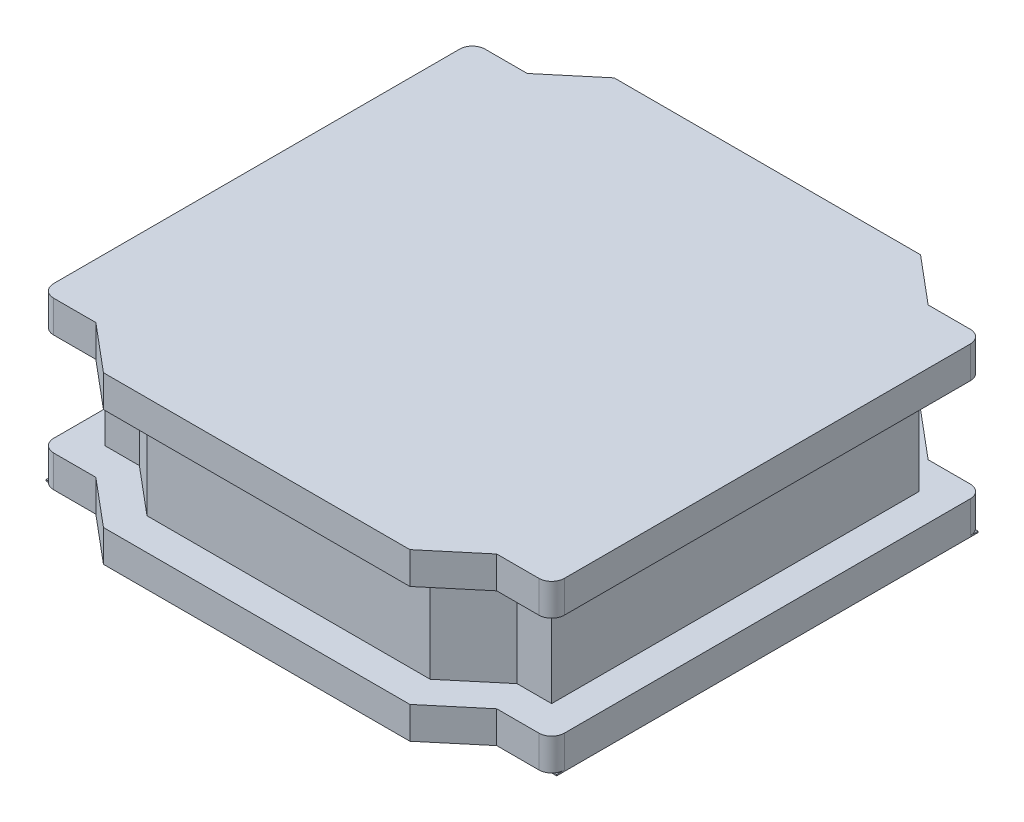
SolidWorks part; units mm, degrees
ref_plane "Alzado" through (0, 0, 0) normal (0, 0, 1) x (1, 0, 0)
ref_plane "Planta" through (0, 0, 0) normal (0, 1, 0) x (1, 0, 0)
ref_plane "Vista lateral" through (0, 0, 0) normal (1, 0, 0) x (0, 0, -1)
sketch "Croquis1" plane through (0, 0, 0) normal (0, 1, 0) x (1, 0, 0)
  line L0 (0.0879, 2.3156) -> (0.0879, -1.9186) construction
  line L1 (-3.3874, 0) -> (5.3457, 0) construction
  line L2 (1.2879, 2) -> (-1.1121, 2)
  line L3 (-1.1121, 2) -> (-1.4821, 1.6895)
  line L4 (-1.4821, 1.6895) -> (-1.8121, 1.6895)
  line L5 (-1.9121, 1.5895) -> (-1.9121, -1.5895)
  line L6 (2.0879, 1.5895) -> (2.0879, -1.5895)
  line L7 (1.658, 1.6895) -> (1.9879, 1.6895)
  line L8 (1.2879, 2) -> (1.658, 1.6895)
  line L9 (1.2879, -2) -> (1.658, -1.6895)
  line L10 (1.658, -1.6895) -> (1.9879, -1.6895)
  line L11 (-1.4821, -1.6895) -> (-1.8121, -1.6895)
  line L12 (-1.1121, -2) -> (-1.4821, -1.6895)
  line L13 (1.2879, -2) -> (-1.1121, -2)
  arc A0 (-1.8121, -1.6895) -> (-1.9121, -1.5895) centre (-1.8121, -1.5895) cw
  arc A1 (1.9879, -1.6895) -> (2.0879, -1.5895) centre (1.9879, -1.5895) ccw
  arc A2 (2.0879, 1.5895) -> (1.9879, 1.6895) centre (1.9879, 1.5895) ccw
  arc A3 (-1.8121, 1.6895) -> (-1.9121, 1.5895) centre (-1.8121, 1.5895) ccw
  point P14 (0.0879, 2)
  point P17 (2.0879, 0)
  point P18 (-1.9121, 0)
  point P20 (0.0879, -2)
  point P23 (-1.9121, -1.6895)
  point P26 (2.0879, -1.6895)
  point P29 (2.0879, 1.6895)
  point P32 (-1.9121, 1.6895)
  dimension "D5" = 0.1
  dimension "D1" = 2
  dimension "D2" = 2
  dimension "D3" = 40
  dimension "D4" = 1.2
extrude "Saliente-Extruir1" add sketch "Croquis1" along normal blind 0.25
sketch "Croquis3" plane through (0, 0.25, 0) normal (0, 1, 0) x (1, 0, 0)
  line L24 (-1.0211, -1.75) -> (1.1969, -1.75)
  line L25 (1.1969, -1.75) -> (1.567, -1.4395)
  line L26 (1.567, -1.4395) -> (1.8379, -1.4395)
  line L27 (1.8379, -1.4395) -> (1.8379, 1.4395)
  line L28 (1.8379, 1.4395) -> (1.567, 1.4395)
  line L29 (1.567, 1.4395) -> (1.1969, 1.75)
  line L30 (1.1969, 1.75) -> (-1.0211, 1.75)
  line L31 (-1.0211, 1.75) -> (-1.3911, 1.4395)
  line L32 (-1.3911, 1.4395) -> (-1.6621, 1.4395)
  line L33 (-1.6621, 1.4395) -> (-1.6621, -1.4395)
  line L34 (-1.6621, -1.4395) -> (-1.3911, -1.4395)
  line L35 (-1.3911, -1.4395) -> (-1.0211, -1.75)
  line L36 (-1.0211, -1.75) -> (1.1969, -1.75)
  line L37 (1.1969, -1.75) -> (1.567, -1.4395)
  line L38 (1.567, -1.4395) -> (1.8379, -1.4395)
  line L39 (1.8379, -1.4395) -> (1.8379, 1.4395)
  line L40 (1.8379, 1.4395) -> (1.567, 1.4395)
  line L41 (1.567, 1.4395) -> (1.1969, 1.75)
  line L42 (1.1969, 1.75) -> (-1.0211, 1.75)
  line L43 (-1.0211, 1.75) -> (-1.3911, 1.4395)
  line L44 (-1.3911, 1.4395) -> (-1.6621, 1.4395)
  line L45 (-1.6621, 1.4395) -> (-1.6621, -1.4395)
  line L46 (-1.6621, -1.4395) -> (-1.3911, -1.4395)
  line L47 (-1.3911, -1.4395) -> (-1.0211, -1.75)
  dimension "D1" = 0.25
extrude "Saliente-Extruir3" add sketch "Croquis3" along normal blind 0.8
ref_plane "Plano1" through (0, 1.3, 0) normal (0, 1, 0) x (1, 0, 0)
sketch "Croquis2" plane through (0, 1.3, 0) normal (0, 1, 0) x (1, 0, 0)
  line L12 (-1.1121, -2) -> (1.2879, -2)
  line L13 (1.2879, -2) -> (1.658, -1.6895)
  line L14 (1.658, -1.6895) -> (1.9879, -1.6895)
  line L15 (2.0879, -1.5895) -> (2.0879, 1.5895)
  line L16 (1.9879, 1.6895) -> (1.658, 1.6895)
  line L17 (1.658, 1.6895) -> (1.2879, 2)
  line L18 (1.2879, 2) -> (-1.1121, 2)
  line L19 (-1.1121, 2) -> (-1.4821, 1.6895)
  line L20 (-1.4821, 1.6895) -> (-1.8121, 1.6895)
  line L21 (-1.9121, 1.5895) -> (-1.9121, -1.5895)
  line L22 (-1.8121, -1.6895) -> (-1.4821, -1.6895)
  line L23 (-1.4821, -1.6895) -> (-1.1121, -2)
  line L24 (-1.1121, -2) -> (1.2879, -2)
  line L25 (1.2879, -2) -> (1.658, -1.6895)
  line L26 (1.658, -1.6895) -> (1.9879, -1.6895)
  line L27 (2.0879, -1.5895) -> (2.0879, 1.5895)
  line L28 (1.9879, 1.6895) -> (1.658, 1.6895)
  line L29 (1.658, 1.6895) -> (1.2879, 2)
  line L30 (1.2879, 2) -> (-1.1121, 2)
  line L31 (-1.1121, 2) -> (-1.4821, 1.6895)
  line L32 (-1.4821, 1.6895) -> (-1.8121, 1.6895)
  line L33 (-1.9121, 1.5895) -> (-1.9121, -1.5895)
  line L34 (-1.8121, -1.6895) -> (-1.4821, -1.6895)
  line L35 (-1.4821, -1.6895) -> (-1.1121, -2)
  arc A4 (1.9879, -1.6895) -> (2.0879, -1.5895) centre (1.9879, -1.5895) ccw
  arc A5 (1.9879, -1.6895) -> (2.0879, -1.5895) centre (1.9879, -1.5895) ccw
  arc A6 (2.0879, 1.5895) -> (1.9879, 1.6895) centre (1.9879, 1.5895) ccw
  arc A7 (2.0879, 1.5895) -> (1.9879, 1.6895) centre (1.9879, 1.5895) ccw
  arc A8 (-1.8121, 1.6895) -> (-1.9121, 1.5895) centre (-1.8121, 1.5895) ccw
  arc A9 (-1.8121, 1.6895) -> (-1.9121, 1.5895) centre (-1.8121, 1.5895) ccw
  arc A10 (-1.9121, -1.5895) -> (-1.8121, -1.6895) centre (-1.8121, -1.5895) ccw
  arc A11 (-1.9121, -1.5895) -> (-1.8121, -1.6895) centre (-1.8121, -1.5895) ccw
  dimension "D1" = 0
extrude "Saliente-Extruir2" add sketch "Croquis2" against normal blind 0.25 separate body
sketch "Croquis4" plane through (0, 0, 0) normal (0, -1, 0) x (1, 0, 0)
  line L0 (0.0879, 1.1918) -> (0.0879, -0.8163) construction
  line L1 (2.0879, -1.65) -> (0.8879, -1.65)
  line L2 (2.0879, -1.65) -> (2.0879, 1.65)
  line L3 (2.0879, 1.65) -> (0.8879, 1.65)
  line L4 (0.8879, -1.65) -> (0.8879, 1.65)
  line L5 (0, 0) -> (2.5141, 0) construction
  line L6 (-1.9121, 1.65) -> (-0.7121, 1.65)
  line L7 (-0.7121, -1.65) -> (-0.7121, 1.65)
  line L8 (-1.9121, -1.65) -> (-0.7121, -1.65)
  line L9 (-1.9121, -1.65) -> (-1.9121, 1.65)
  line L11 (-1.1121, 2) -> (1.2879, 2) construction
  point P4 (0, 0)
  point P16 (0.0879, 2)
  dimension "D1" = 3.3
  dimension "D2" = 1.2
  dimension "D3" = 1.6
extrude "Saliente-Extruir4" add sketch "Croquis4" along normal blind 0.01
